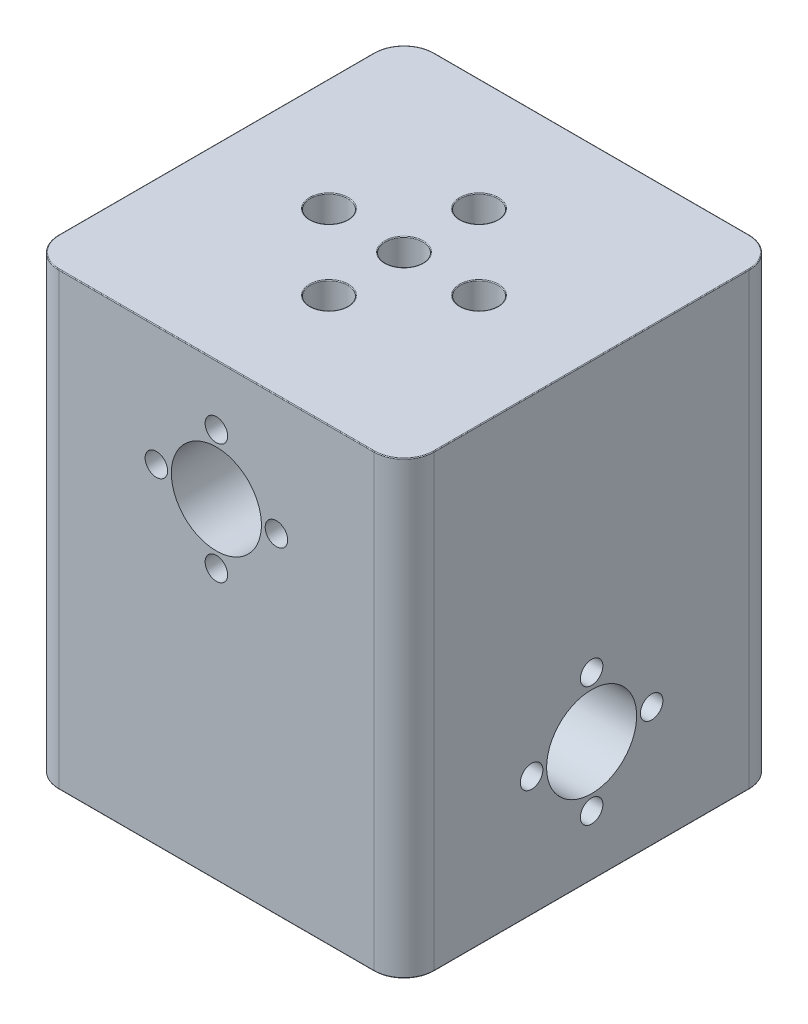
SolidWorks part; units mm, degrees
ref_plane "Front Plane" through (0, 0, 0) normal (0, 0, 1) x (1, 0, 0)
ref_plane "Top Plane" through (0, 0, 0) normal (0, 1, 0) x (1, 0, 0)
ref_plane "Right Plane" through (0, 0, 0) normal (1, 0, 0) x (0, 0, -1)
sketch "Sketch1" plane through (0, 0, 0) normal (0, 1, 0) x (1, 0, 0)
  line L1 (-25, 25) -> (25, 25)
  line L2 (-25, 25) -> (-25, -25)
  line L3 (-25, -25) -> (25, -25)
  line L4 (25, 25) -> (25, -25)
  line L5 (-25, 25) -> (25, -25) construction
  line L6 (-25, -25) -> (25, 25) construction
  point P0 (0, 0)
  dimension "D1" = 50
  dimension "D2" = 50
extrude "Boss-Extrude1" add sketch "Sketch1" along normal blind 60
sketch "Sketch2" plane through (0, 0, 0) normal (0, -1, 0) x (1, 0, 0)
  circle A0 centre (0, 10) radius 2.5
  circle A1 centre (0, -10) radius 2.5
  circle A2 centre (10, 0) radius 2.5
  circle A3 centre (-10, 0) radius 2.5
  circle A4 centre (0, 0) radius 2.5
  dimension "D1" = 5
  dimension "D2" = 5
  dimension "D3" = 5
  dimension "D4" = 5
  dimension "D9" = 5
  dimension "D5" = 20
  dimension "D6" = 20
  dimension "D7" = 10
  dimension "D8" = 10
extrude "Cut-Extrude1" cut sketch "Sketch2" against normal blind 15
sketch "Sketch9" plane through (0, 60, 0) normal (0, 1, 0) x (1, 0, 0)
  line L0 (0, 25) -> (0, -25) construction
  line L1 (25, 25) -> (-25, 25) construction
  line L2 (-25, -25) -> (25, -25) construction
  line L3 (-25, 0) -> (25, 0) construction
  line L4 (-25, 25) -> (-25, -25) construction
  line L5 (25, -25) -> (25, 25) construction
  circle A0 centre (0, 10) radius 2.5
  circle A1 centre (0, -10) radius 2.5
  circle A2 centre (10, 0) radius 2.5
  circle A3 centre (-10, 0) radius 2.5
  circle A4 centre (0, 0) radius 2.5
  dimension "D1" = 5
  dimension "D2" = 5
  dimension "D3" = 5
  dimension "D4" = 5
  dimension "D5" = 5
  dimension "D6" = 10
  dimension "D7" = 10
  dimension "D8" = 10
  dimension "D9" = 10
  dimension "D10" = 10
  dimension "D11" = 10
  dimension "D12" = 0
  dimension "D13" = 0
extrude "Cut-Extrude6" cut sketch "Sketch9" against normal blind 15
sketch "Sketch4" plane through (-25, 0, 0) normal (-1, 0, 0) x (0, 0, 1)
  line L0 (-25, 0) -> (25, 0) construction
  circle A0 centre (0, 16) radius 6
  dimension "D1" = 12
  dimension "D2" = 16
extrude "Cut-Extrude2" cut sketch "Sketch4" against normal up to next
sketch "Sketch10" plane through (0, 0, -25) normal (0, 0, -1) x (-1, 0, 0)
  line L0 (0, 60) -> (0, 0) construction
  line L1 (-25, 60) -> (25, 60) construction
  line L2 (-25, 0) -> (25, 0) construction
  circle A0 centre (0, 44) radius 6
  dimension "D1" = 12
  dimension "D2" = 16
extrude "Cut-Extrude7" cut sketch "Sketch10" against normal through all contours A0
sketch "Sketch5" plane through (-25, 0, 0) normal (-1, 0, 0) x (0, 0, 1)
  circle A0 centre (-8, 16) radius 1.5
  circle A1 centre (8, 16) radius 1.5
  circle A2 centre (0, 8) radius 1.5
  circle A3 centre (0, 24) radius 1.5
  point P15 (0, 16)
  dimension "D5" = 3
  dimension "D6" = 3
  dimension "D7" = 3
  dimension "D8" = 3
  dimension "D1" = 16
  dimension "D2" = 16
  dimension "D3" = 8
  dimension "D4" = 8
extrude "Cut-Extrude3" cut sketch "Sketch5" against normal blind 10
sketch "Sketch11" plane through (0, 0, -25) normal (0, 0, -1) x (-1, 0, 0)
  circle A0 centre (-8, 44) radius 1.5
  circle A1 centre (8, 44) radius 1.5
  circle A2 centre (0, 36) radius 1.5
  circle A3 centre (0, 52) radius 1.5
  circle A4 centre (0, 44) radius 6 construction
  point P8 (0, 44)
  point P11 (0, 0)
  point P12 (0, 0)
  point P15 (0, 0)
  point P16 (0, 0)
  dimension "D5" = 3
  dimension "D6" = 3
  dimension "D7" = 3
  dimension "D8" = 3
  dimension "D10" = 8
  dimension "D1" = 16
  dimension "D2" = 16
  dimension "D3" = 8
  dimension "D4" = 8
  dimension "D9" = 0
extrude "Cut-Extrude8" cut sketch "Sketch11" against normal blind 10
sketch "Sketch6" plane through (25, 0, 0) normal (1, 0, 0) x (0, 0, -1)
  circle A0 centre (-8, 16) radius 1.5
  circle A1 centre (8, 16) radius 1.5
  circle A2 centre (0, 24) radius 1.5
  circle A3 centre (0, 8) radius 1.5
  circle A4 centre (0, 16) radius 6 construction
  point P11 (0, 16)
  dimension "D1" = 3
  dimension "D2" = 3
  dimension "D3" = 3
  dimension "D4" = 3
  dimension "D5" = 16
  dimension "D6" = 16
  dimension "D7" = 8
  dimension "D8" = 8
extrude "Cut-Extrude4" cut sketch "Sketch6" against normal blind 10 contours A2 | A0 | A3 | A1
sketch "Sketch12" plane through (0, 0, 25) normal (0, 0, 1) x (1, 0, 0)
  circle A0 centre (-8, 44) radius 1.5
  circle A1 centre (8, 44) radius 1.5
  circle A2 centre (0, 36) radius 1.5
  circle A3 centre (0, 52) radius 1.5
  circle A4 centre (0, 44) radius 6 construction
  point P8 (0, 44)
  dimension "D5" = 3
  dimension "D6" = 3
  dimension "D7" = 3
  dimension "D8" = 3
  dimension "D11" = 8
  dimension "D1" = 16
  dimension "D2" = 16
  dimension "D3" = 8
  dimension "D4" = 8
  dimension "D9" = 0
  dimension "D10" = 0
extrude "Cut-Extrude9" cut sketch "Sketch12" against normal blind 10
fillet "Fillet1" radius 4 4 edges at (25, 30, 25) (-25, 30, 25) (-25, 30, -25) (25, 30, -25)
fillet "Fillet2" radius 0.1 26 edges at (23.8284, 0, -23.8284) (0, 0, -25) (-23.8284, 0, -23.8284) (-25, 0, 0) (-23.8284, 0, 23.8284) (0, 0, 25) (23.8284, 0, 23.8284) (25, 0, 0) (0, 0, -12.5) (10, 0, -2.5) (-10, 0, -2.5) (0, 0, -2.5) (0, 0, 7.5) (-23.8284, 60, 23.8284) (-25, 60, 0) (-23.8284, 60, -23.8284) (0, 60, -25) (23.8284, 60, -23.8284) (25, 60, 0) (23.8284, 60, 23.8284) (0, 60, 25) (0, 60, 12.5) (10, 60, 2.5) (-10, 60, 2.5) (0, 60, 2.5) (0, 60, -7.5)
